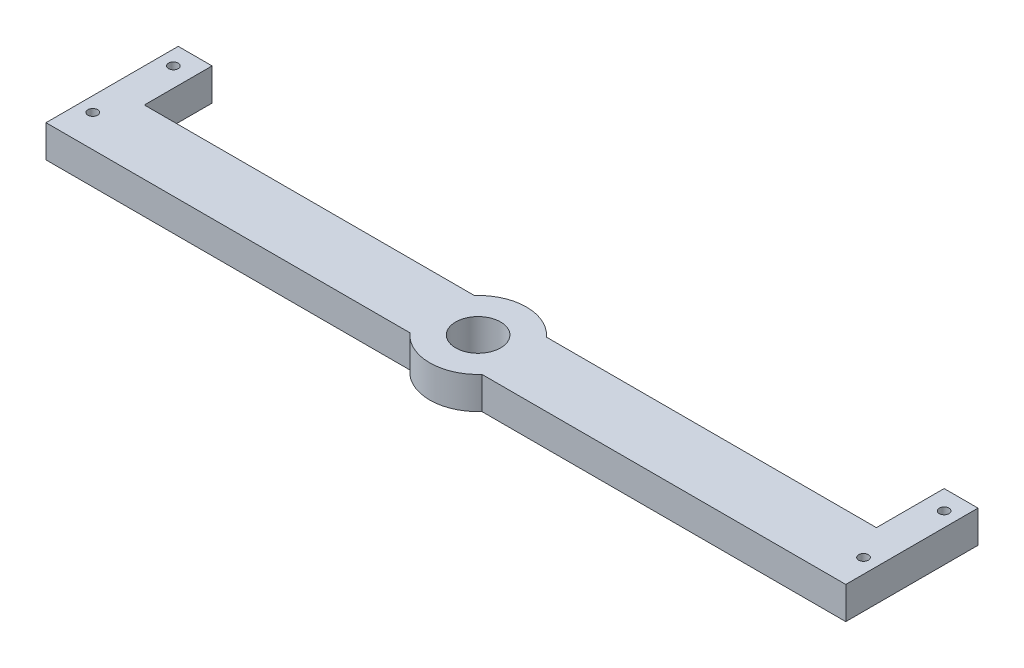
SolidWorks part; units mm, degrees
material "ABS PC"
ref_plane "Front Plane" through (0, 0, 0) normal (0, 0, 1) x (1, 0, 0)
ref_plane "Top Plane" through (0, 0, 0) normal (0, 1, 0) x (1, 0, 0)
ref_plane "Right Plane" through (0, 0, 0) normal (1, 0, 0) x (0, 0, -1)
sketch "Sketch1" plane through (0, 0, 0) normal (0, 1, 0) x (1, 0, 0)
  line L0 (0, 0) -> (0, 7.5) construction
  line L1 (-124, -10) -> (-11.1803, -10)
  line L2 (-124, -10) -> (-124, 10)
  line L4 (124, -10) -> (124, 10)
  line L5 (-124, -10) -> (124, 10) construction
  line L6 (-124, 10) -> (124, -10) construction
  line L7 (-124, 0) -> (-119.5, 0) construction
  line L8 (11.1803, 10) -> (113.5, 10)
  line L9 (11.1803, -10) -> (124, -10)
  line L10 (-119.5, 0) -> (-119.5, 25) construction
  line L11 (-124, 10) -> (-124, 31)
  line L12 (-124, 31) -> (-113.5, 31)
  line L13 (-113.5, 31) -> (-113.5, 10)
  line L14 (124, 10) -> (124, 31)
  line L15 (124, 31) -> (113.5, 31)
  line L16 (113.5, 31) -> (113.5, 10)
  line L17 (-113.5, 10) -> (-11.1803, 10)
  circle A0 centre (-119.5, 0) radius 1.5
  circle A1 centre (119.5, 0) radius 1.5
  circle A2 centre (0, 0) radius 6.975
  arc A3 (-11.1803, -10) -> (11.1803, -10) centre (0, 0) ccw
  arc A4 (11.1803, 10) -> (-11.1803, 10) centre (0, 0) ccw
  circle A5 centre (-119.5, 25) radius 1.5
  circle A6 centre (119.5, 25) radius 1.5
  point P0 (0, 0)
  dimension "D4" = 3
  dimension "D5" = 13.95
  dimension "D6" = 30
  dimension "D8" = 3
  dimension "D1" = 20
  dimension "D2" = 248
  dimension "D3" = 4.5
  dimension "D7" = 25
  dimension "D9" = 6
  dimension "D10" = 6
extrude "Boss-Extrude1" add sketch "Sketch1" along normal blind 10
